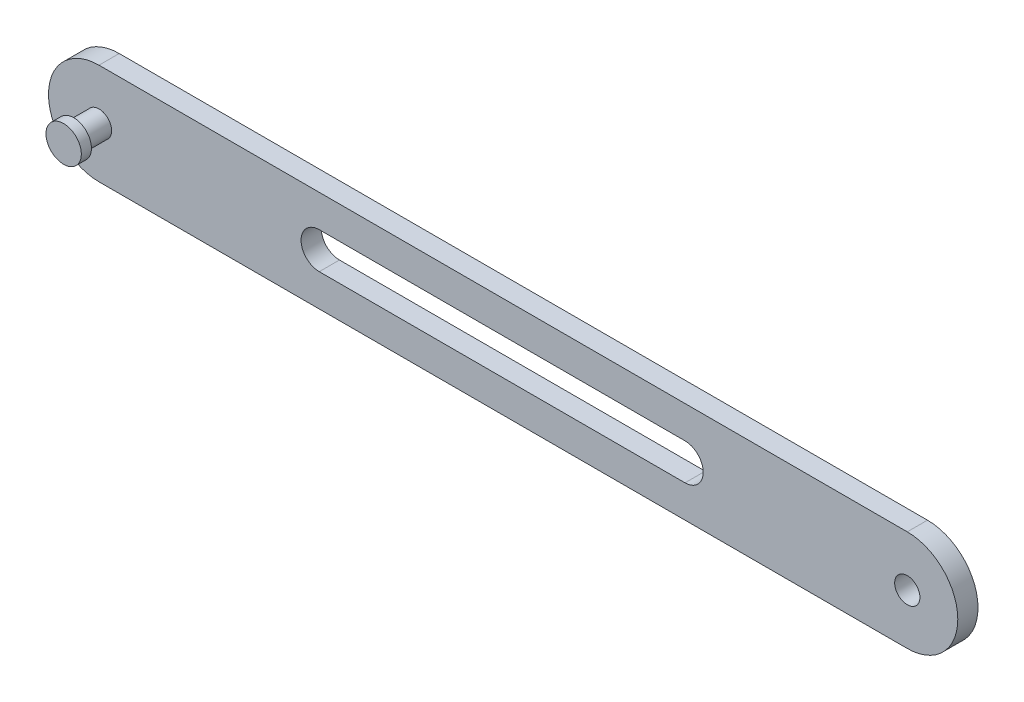
SolidWorks part; units mm, degrees
ref_plane "Front Plane" through (0, 0, 0) normal (0, 0, 1) x (1, 0, 0)
ref_plane "Top Plane" through (0, 0, 0) normal (0, 1, 0) x (1, 0, 0)
ref_plane "Right Plane" through (0, 0, 0) normal (1, 0, 0) x (0, 0, -1)
sketch "Sketch1" plane through (0, 0, 0) normal (0, 0, 1) x (1, 0, 0)
  line L0 (-101.6, 0) -> (101.6, 0) construction
  line L1 (-101.6, 12.7) -> (101.6, 12.7)
  line L2 (-101.6, -12.7) -> (101.6, -12.7)
  arc A0 (-101.6, 12.7) -> (-101.6, -12.7) centre (-101.6, 0) ccw
  arc A1 (101.6, -12.7) -> (101.6, 12.7) centre (101.6, 0) ccw
  point P2 (0, 0)
  dimension "D1" = 203.2
  dimension "D2" = 25.4
extrude "Boss-Extrude1" add sketch "Sketch1" along normal mid plane 5.08 contours L1 A1 L2 A0
sketch "Sketch2" plane through (0, 0, 2.54) normal (0, 0, 1) x (1, 0, 0)
  circle A0 centre (101.6, 0) radius 3.175
  dimension "D1" = 6.35
extrude "Cut-Extrude1" cut sketch "Sketch2" against normal through all contours A0
sketch "Sketch3" plane through (0, 0, 2.54) normal (0, 0, 1) x (1, 0, 0)
  line L0 (-46.228, 0) -> (45.72, 0) construction
  line L1 (-46.228, 4.572) -> (45.72, 4.572)
  line L2 (-46.228, -4.572) -> (45.72, -4.572)
  arc A0 (-46.228, 4.572) -> (-46.228, -4.572) centre (-46.228, 0) ccw
  arc A1 (45.72, -4.572) -> (45.72, 4.572) centre (45.72, 0) ccw
  point P2 (-0.254, 0)
  dimension "D1" = 4.572
  dimension "D2" = 91.948
  dimension "D3" = 55.88
extrude "Cut-Extrude2" cut sketch "Sketch3" against normal through all
sketch "Sketch4" plane through (0, 0, 2.54) normal (0, 0, 1) x (1, 0, 0)
  circle A0 centre (-101.6, 0) radius 3.175
  dimension "D1" = 6.35
extrude "Boss-Extrude2" add sketch "Sketch4" along normal blind 8.89
sketch "Sketch5" plane through (0, 0, 11.43) normal (0, 0, 1) x (1, 0, 0)
  circle A0 centre (-101.6, 0) radius 4.445
  dimension "D1" = 8.89
extrude "Boss-Extrude3" add sketch "Sketch5" against normal blind 2.54
